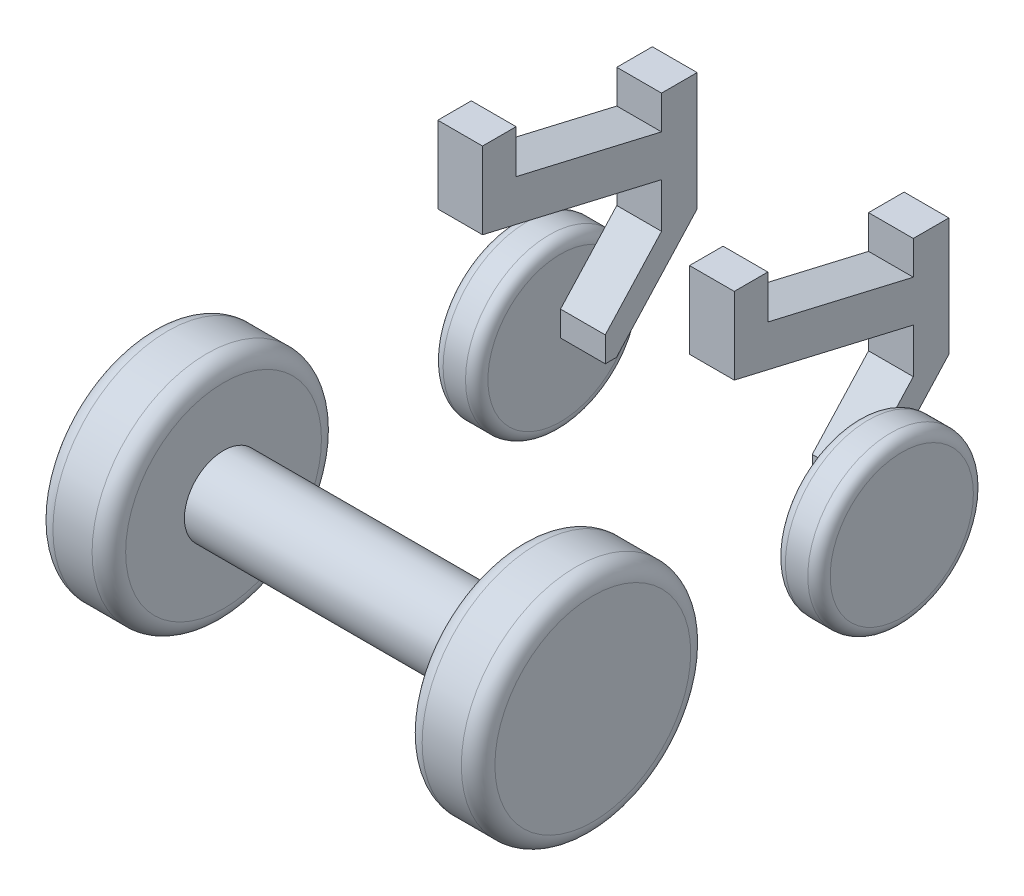
SolidWorks part; units mm, degrees
ref_plane "Front Plane" through (0, 0, 0) normal (0, 0, 1) x (1, 0, 0)
ref_plane "Top Plane" through (0, 0, 0) normal (0, 1, 0) x (1, 0, 0)
ref_plane "Right Plane" through (0, 0, 0) normal (1, 0, 0) x (0, 0, -1)
sketch "Sketch2" plane through (0, 0, 0) normal (1, 0, 0) x (0, 0, -1)
  circle A0 centre (0, 0) radius 130.175
  dimension "D1" = 260.35
extrude "Boss-Extrude1" add sketch "Sketch2" along normal blind 82.55
fillet "Fillet1" radius 19.05 2 edges at (0, 0, -130.175) (82.55, 0, -130.175)
sketch "Sketch3" plane through (0, 0, 0) normal (-1, 0, 0) x (0, 0, 1)
  circle A0 centre (0, 0) radius 44.45
  dimension "D1" = 88.9
extrude "Boss-Extrude2" add sketch "Sketch3" along normal blind 336.55
sketch "Sketch4" plane through (-336.55, 0, 0) normal (-1, 0, 0) x (0, 0, 1)
  circle A0 centre (0, 0) radius 130.175
  dimension "D1" = 260.35
extrude "Boss-Extrude3" add sketch "Sketch4" along normal blind 82.55
fillet "Fillet3" radius 19.05 2 edges at (-419.1, 0, 130.175) (-336.55, 0, 130.175)
sketch "Sketch5" plane through (0, 0, 0) normal (1, 0, 0) x (0, 0, -1)
  line L0 (0, -130.175) -> (1031.7561, -130.175) construction
  circle A0 centre (0, 0) radius 130.175 construction
  circle A1 centre (382.4661, -36.195) radius 93.98
  dimension "D1" = 187.96
  dimension "D3" = 93.98
  dimension "D2" = 384.175
extrude "Boss-Extrude5" add sketch "Sketch5" along normal blind 50.8 separate body
fillet "Fillet4" radius 12.7 2 edges at (50.8, -36.195, -476.4461) (0, -36.195, -476.4461)
sketch "Sketch6" plane through (0, 0, 0) normal (-1, 0, 0) x (0, 0, 1)
  line L0 (-382.4661, -117.475) -> (-382.4661, 101.9656) construction
  line L1 (-277.7802, -36.195) -> (-525.6458, -36.195) construction
  line L2 (-395.1231, -36.195) -> (-476.0275, 62.2281)
  line L3 (-476.0275, 62.2281) -> (-476.0275, 197.9676)
  line L4 (-476.0275, 197.9676) -> (-435.5753, 197.9676)
  line L5 (-435.5753, 197.9676) -> (-435.5753, 62.2281)
  line L6 (-435.5753, 62.2281) -> (-382.4661, -7.7547)
  line L7 (-382.4661, -7.7547) -> (-382.4661, -36.195)
  line L8 (-382.4661, -36.195) -> (-395.1231, -36.195)
  circle A0 centre (-382.4661, -36.195) radius 81.28 construction
  point P9 (0, 0)
  point P15 (0, 0)
  point P16 (0, 0)
sketch "Sketch7" plane through (0, 0, 0) normal (0, 0, 1) x (1, 0, 0)
  line L0 (82.55, 0) -> (-419.1, 0) construction
  line L1 (82.55, -111.125) -> (82.55, 111.125) construction
  line L2 (-419.1, 111.125) -> (-419.1, -111.125) construction
  line L3 (-168.275, 146.3262) -> (-168.275, -127.0644) construction
sketch "Sketch8" plane through (0, 0, 0) normal (0, 1, 0) x (1, 0, 0)
  line L0 (-168.275, 0) -> (-168.275, 504.3474) construction
  line L1 (82.55, 0) -> (-419.1, 0) construction
ref_plane "Plane1" through (-168.275, 0, 0) normal (-1, 0, 0) x (0, 0, 1)
sketch "Sketch9" plane through (-336.55, 0, 0) normal (1, 0, 0) x (0, 0, -1)
  line L0 (0, 0) -> (0, -236.9187) construction
  line L1 (0, -130.175) -> (502.5938, -130.175) construction
  circle A0 centre (382.4661, -36.195) radius 95.148
  dimension "D1" = 130.175
  dimension "D2" = 384.175
  dimension "D3" = 93.98
extrude "Boss-Extrude7" add sketch "Sketch9" against normal blind 50.8 separate body
fillet "Fillet5" radius 12.7 2 edges at (-387.35, -36.195, -477.6141) (-336.55, -36.195, -477.6141)
sketch "Sketch10" plane through (-336.55, 0, 0) normal (1, 0, 0) x (0, 0, -1)
  line L0 (382.4661, -36.195) -> (382.4661, 73.5116) construction
  line L1 (382.4661, -36.195) -> (545.4849, -36.195) construction
  line L2 (382.4661, -36.195) -> (382.4661, -7.747)
  line L3 (382.4661, -7.747) -> (446.3333, 62.103)
  line L4 (446.3333, 62.103) -> (446.3333, 197.993)
  line L5 (446.3333, 197.993) -> (486.7193, 197.993)
  line L6 (486.7193, 197.993) -> (486.7193, 63.9345)
  line L7 (486.7193, 63.9345) -> (395.1661, -36.195)
  line L8 (395.1661, -36.195) -> (382.4661, -36.195)
  dimension "D1" = 28.448
  dimension "D2" = 12.7
  dimension "D3" = 98.298
  dimension "D4" = 234.188
  dimension "D5" = 40.386
extrude "Boss-Extrude8" add sketch "Sketch10" along normal blind 50.8 separate body
sketch "Sketch11" plane through (-285.75, 0, 0) normal (1, 0, 0) x (0, 0, -1)
  line L0 (446.3333, 112.903) -> (243.1333, 160.3163)
  line L1 (446.3333, 197.993) -> (446.3333, 62.103) construction
  line L2 (243.1333, 160.3163) -> (243.1333, 247.5653)
  line L3 (243.1333, 247.5653) -> (281.2333, 247.5653)
  line L4 (281.2333, 247.5653) -> (281.2333, 198.4163)
  line L5 (281.2333, 198.4163) -> (446.3333, 159.893)
  line L6 (446.3333, 159.893) -> (446.3333, 112.903)
  point P4 (0, 0)
  point P9 (0, 0)
  dimension "D1" = 203.2
  dimension "D2" = 50.8
  dimension "D3" = 38.1
  dimension "D4" = 38.1
  dimension "D5" = 38.1
  dimension "D6" = 87.249
extrude "Boss-Extrude9" add sketch "Sketch11" against normal blind 50.8
mirror "Mirror15" about plane through (-168.275, 0, 0) normal (-1, 0, 0) of bodies 111
